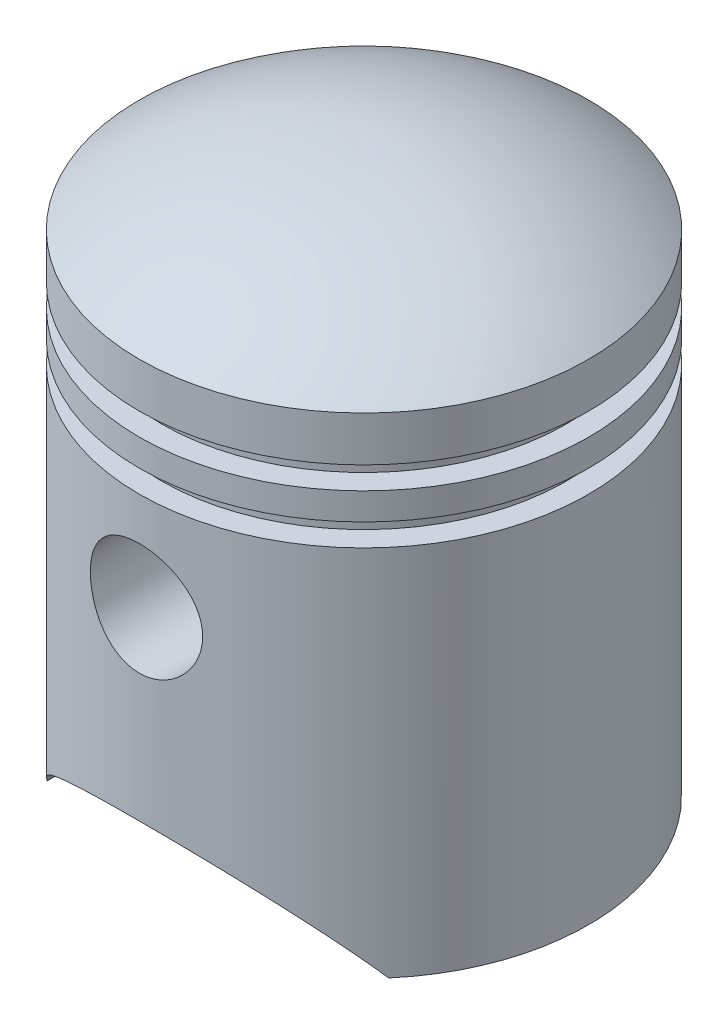
SolidWorks part; units mm, degrees
ref_plane "Front Plane" through (0, 0, 0) normal (0, 0, 1) x (1, 0, 0)
ref_plane "Top Plane" through (0, 0, 0) normal (0, 1, 0) x (1, 0, 0)
ref_plane "Right Plane" through (0, 0, 0) normal (1, 0, 0) x (0, 0, -1)
sketch "Sketch1" plane through (0, 0, 0) normal (0, 0, 1) x (1, 0, 0)
  line L0 (25, 0) -> (25, 41.5)
  line L1 (25, 49.5) -> (22.5, 49.5)
  line L2 (22.5, 49.5) -> (22.5, 47)
  line L3 (22.5, 47) -> (25, 47)
  line L4 (25, 44) -> (22.5, 44)
  line L5 (22.5, 44) -> (22.5, 41.5)
  line L6 (22.5, 41.5) -> (25, 41.5)
  line L7 (25, 49.5) -> (25, 54.5)
  line L8 (25, 44) -> (25, 47)
  line L9 (23, 0) -> (23, 39.5)
  line L10 (20.5, 39.5) -> (23, 39.5)
  line L11 (20.5, 45.5) -> (20.5, 39.5)
  line L12 (20.5, 45.5) -> (20.5, 45.5)
  line L13 (20.5, 45.5) -> (20.5, 45.5)
  line L14 (20.5, 45.5) -> (20.5, 45.5)
  line L15 (20.5, 51.5) -> (20.5, 45.5)
  line L16 (23, 51.5) -> (20.5, 51.5)
  line L17 (23, 51.5) -> (23, 53.4845)
  line L18 (25, 0) -> (23, 0)
  line L20 (0, 62.5) -> (0, 60.4994)
  arc A0 (25, 54.5) -> (0, 62.5) centre (0.9839, 22.5121) ccw
  arc A1 (23, 53.4845) -> (0, 60.4994) centre (0.9839, 22.5121) ccw
  arc A2 (23, 53.4845) -> (0.0492, 60.5006) centre (0.9839, 22.5121) ccw construction
  dimension "D4" = 40
  dimension "D1" = 25
  dimension "D2" = 62.5
  dimension "D3" = 54.5
  dimension "D5" = 5
  dimension "D6" = 2.5
  dimension "D7" = 2.5
  dimension "D8" = 3
  dimension "D9" = 2.5
  dimension "D10" = 2
revolve "Revolve1" add sketch "Sketch1" angle 360 about L20
sketch "Sketch2" plane through (0, 0, 0) normal (0, 0, 1) x (1, 0, 0)
  line L0 (-25, 0) -> (25, 0) construction
  line L1 (-19, 0) -> (19, 0)
  circle A0 centre (0, 30.5) radius 6.25
  arc A1 (-19, 0) -> (19, 0) centre (0, -13.05) cw
  point P5 (0, 10)
  dimension "D1" = 12.5
  dimension "D2" = 32
  dimension "D3" = 38
  dimension "D4" = 10
extrude "Cut-Extrude1" cut sketch "Sketch2" against normal through all both and the other way through all
sketch "Sketch3" plane through (0, 0, 0) normal (0, 0, 1) x (1, 0, 0)
  circle A0 centre (0, 30.5) radius 7.25
  circle A1 centre (0, 30.5) radius 6.25
  dimension "D1" = 14.5
  dimension "D2" = 12.5
extrude "Boss-Extrude1" add sketch "Sketch3" along normal up to surface (11.9257 mm away) from offset 12
mirror "Mirror1" about plane through (0, 0, 0) normal (0, 0, 1) of "Boss-Extrude1"
